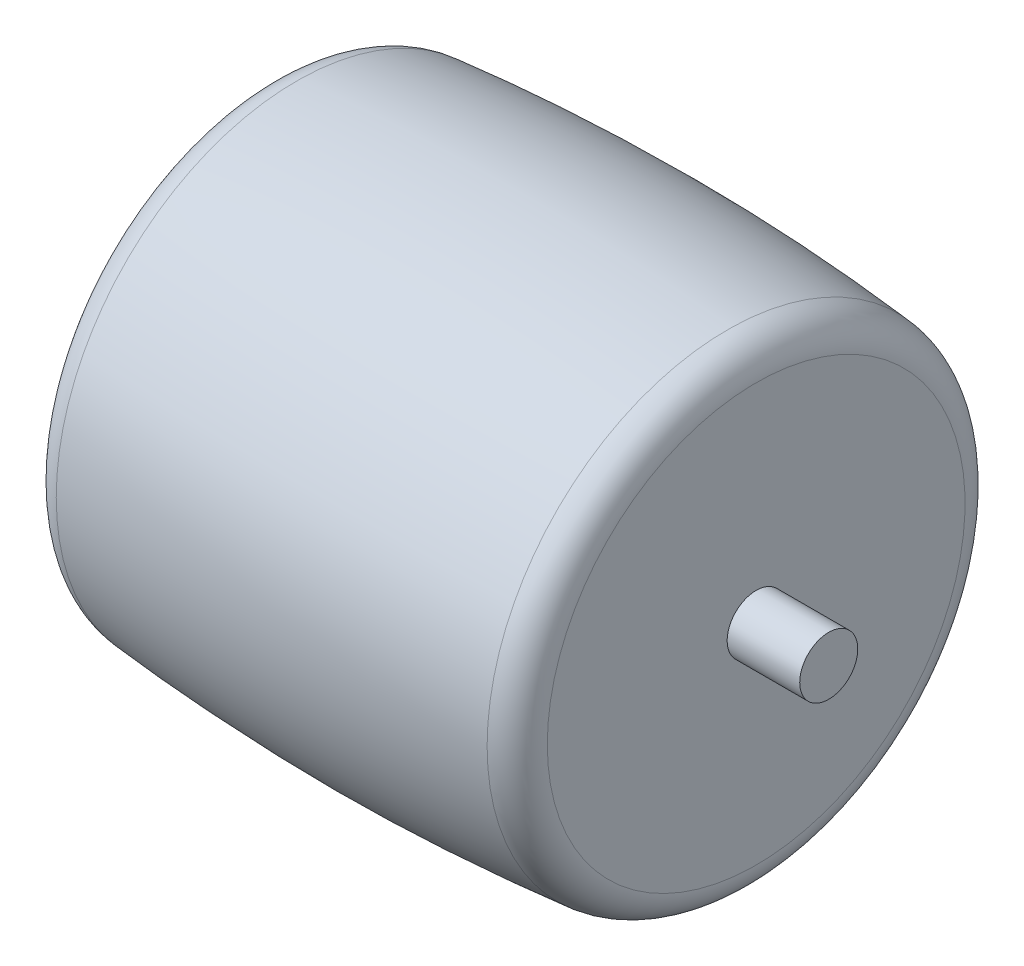
SolidWorks part; units mm, degrees
ref_plane "前视基准面" through (0, 0, 0) normal (0, 0, 1) x (1, 0, 0)
ref_plane "上视基准面" through (0, 0, 0) normal (0, 1, 0) x (1, 0, 0)
ref_plane "右视基准面" through (0, 0, 0) normal (1, 0, 0) x (0, 0, -1)
sketch "草图1" plane through (0, 0, 0) normal (0, 1, 0) x (1, 0, 0)
  line L0 (-12, 0) -> (12, 0)
  line L1 (12, 0) -> (12, 1.1)
  line L2 (12, 1.1) -> (9.25, 1.1)
  line L3 (9.25, 1.1) -> (9.25, 7.9159)
  line L5 (-9.25, 7.916) -> (-9.25, 1.1)
  line L6 (-9.25, 1.1) -> (-12, 1.1)
  line L7 (-12, 1.1) -> (-12, 0)
  line L8 (0, 0) -> (0, 13.4688) construction
  arc A0 (9.25, 7.9159) -> (8.1641, 9.1105) centre (8.05, 7.9159) ccw
  arc A1 (-8.164, 9.1106) -> (-9.25, 7.916) centre (-8.05, 7.916) ccw
  spline S0 degree 3 poles (8.1641, 9.1105) (5.5354, 9.3615) (0.0262, 9.641) (-5.5876, 9.3565) (-8.164, 9.1106) knots 0.058704 0.058704 0.058704 0.058704 0.499985 0.941264 0.941264 0.941264 0.941264
  dimension "D5" = 1.2
  dimension "D9" = 16.3528
  dimension "D12" = 8.1641
  dimension "D1" = 18.5
  dimension "D2" = 2.75
  dimension "D3" = 2.75
  dimension "D4" = 9.5
  dimension "D6" = 7.916
  dimension "D7" = 7.9159
  dimension "D8" = 8.164
  dimension "D10" = 1.1
  dimension "D11" = 1.1
revolve "旋转1" add sketch "草图1" angle 360 about L0
